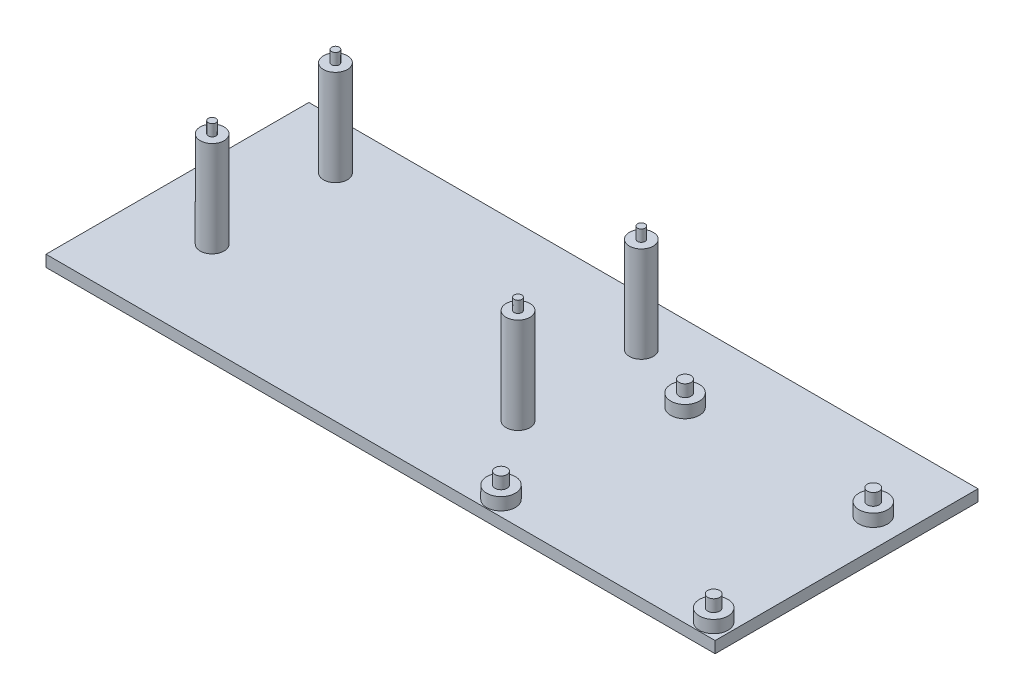
SolidWorks part; units mm, degrees
ref_plane "Front" through (0, 0, 0) normal (0, 0, 1) x (1, 0, 0)
ref_plane "Top" through (0, 0, 0) normal (0, 1, 0) x (1, 0, 0)
ref_plane "Right" through (0, 0, 0) normal (1, 0, 0) x (0, 0, -1)
sketch "Sketch1" plane through (0, 0, 0) normal (0, 1, 0) x (1, 0, 0)
  line L1 (-70, -27.5) -> (70, -27.5)
  line L2 (-70, -27.5) -> (-70, 27.5)
  line L3 (-70, 27.5) -> (70, 27.5)
  line L4 (70, -27.5) -> (70, 27.5)
  point P4 (0, -27.5)
  point P6 (-70, 0)
  dimension "D1" = 140
  dimension "D2" = 55
extrude "Boss-Extrude1" add sketch "Sketch1" along normal blind 2.4 contours L3 L4 L1 L2
sketch "Sketch2" plane through (0, 2.4, 0) normal (0, 1, 0) x (1, 0, 0)
  line L0 (22, -24.3) -> (66.5, -24.3) construction
  line L1 (24.56, 11.65) -> (63.94, 11.65) construction
  line L2 (44.25, 11.65) -> (44.25, -24.3) construction
  line L3 (-70, -27.5) -> (70, -27.5) construction
  line L4 (70, -27.5) -> (70, 27.5) construction
  circle A0 centre (66.5, -24.3) radius 3
  circle A1 centre (63.94, 11.65) radius 3
  circle A2 centre (22, -24.3) radius 3
  circle A3 centre (24.56, 11.65) radius 3
  dimension "D1" = 6
  dimension "D2" = 44.5
  dimension "D3" = 39.38
  dimension "D4" = 35.95
  dimension "D5" = 3.2
  dimension "D6" = 3.5
extrude "Boss-Extrude2" add sketch "Sketch2" along normal blind 2.6
sketch "Sketch3" plane through (0, 5, 0) normal (0, 1, 0) x (1, 0, 0)
  circle A0 centre (22, -24.3) radius 1.25
  circle A1 centre (24.56, 11.65) radius 1.25
  circle A2 centre (66.5, -24.3) radius 1.25
  circle A3 centre (63.94, 11.65) radius 1.25
  dimension "D1" = 2.5
extrude "Boss-Extrude3" add sketch "Sketch3" along normal blind 2.5
sketch "Sketch4" plane through (0, 2.4, 0) normal (0, 1, 0) x (1, 0, 0)
  line L0 (-54.44, -8.3) -> (-54.44, 17.5) construction
  line L1 (-54.44, 17.5) -> (9.56, 17.5) construction
  line L2 (9.56, 17.5) -> (9.56, -8.3) construction
  line L3 (9.56, -8.3) -> (-54.44, -8.3) construction
  line L4 (-70, 27.5) -> (70, 27.5) construction
  circle A0 centre (9.56, 17.5) radius 2.5
  circle A1 centre (-54.44, 17.5) radius 2.5
  circle A2 centre (-54.44, -8.3) radius 2.5
  circle A3 centre (9.56, -8.3) radius 2.5
  circle A4 centre (24.56, 11.65) radius 3 construction
  dimension "D3" = 5
  dimension "D4" = 15
  dimension "D1" = 64
  dimension "D2" = 25.8
  dimension "D5" = 10
extrude "Boss-Extrude4" add sketch "Sketch4" along normal blind 20
sketch "Sketch5" plane through (0, 22.4, 0) normal (0, 1, 0) x (1, 0, 0)
  circle A0 centre (9.56, -8.3) radius 0.8
  circle A1 centre (9.56, 17.5) radius 0.8
  circle A2 centre (-54.44, 17.5) radius 0.8
  circle A3 centre (-54.44, -8.3) radius 0.8
  dimension "D1" = 1.6
extrude "Boss-Extrude5" add sketch "Sketch5" along normal blind 2.4
